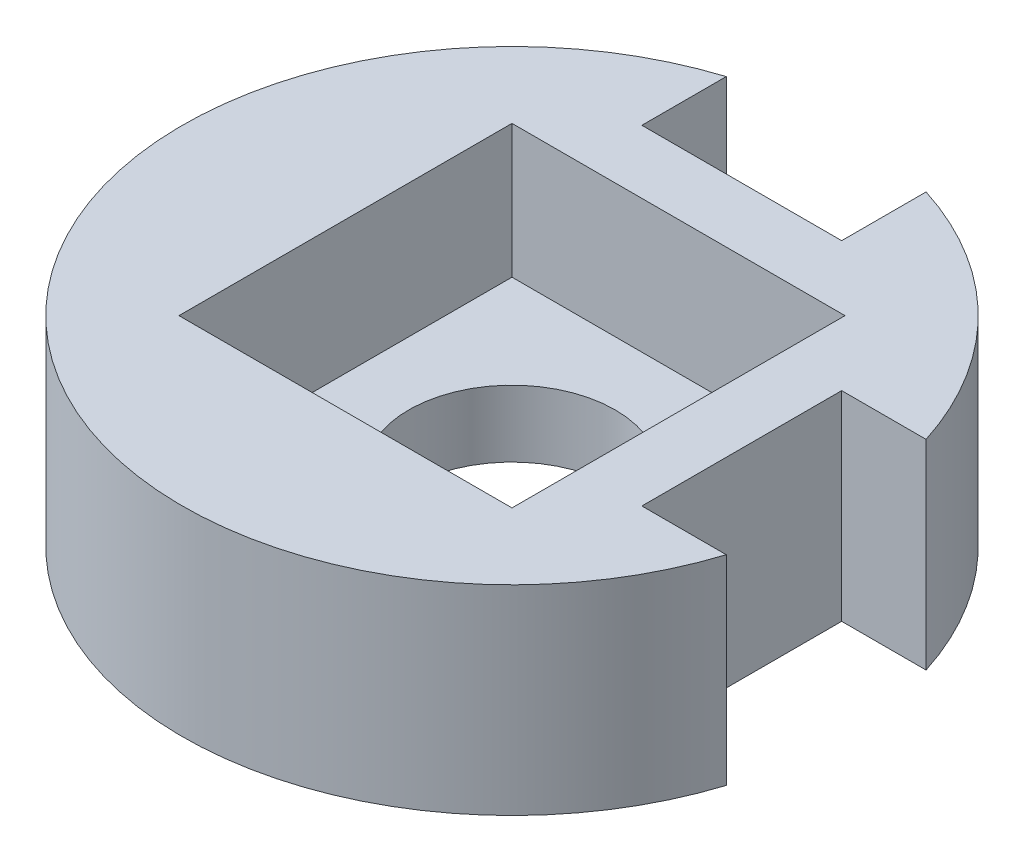
SolidWorks part; units mm, degrees
ref_plane "Front Plane" through (0, 0, 0) normal (0, 0, 1) x (1, 0, 0)
ref_plane "Top Plane" through (0, 0, 0) normal (0, 1, 0) x (1, 0, 0)
ref_plane "Right Plane" through (0, 0, 0) normal (1, 0, 0) x (0, 0, -1)
sketch "Sketch1" plane through (0, 0, 0) normal (0, 1, 0) x (1, 0, 0)
  line L3 (6.9, 3) -> (12.9, 3)
  line L4 (6.9, 3) -> (6.9, -3)
  line L5 (6.9, -3) -> (12.9, -3)
  line L6 (12.9, 3) -> (12.9, -3)
  line L7 (6.9, 3) -> (12.9, -3) construction
  line L8 (6.9, -3) -> (12.9, 3) construction
  line L9 (-3, 12.9) -> (3, 12.9)
  line L10 (-3, 12.9) -> (-3, 6.9)
  line L11 (-3, 6.9) -> (3, 6.9)
  line L12 (3, 12.9) -> (3, 6.9)
  line L13 (-3, 12.9) -> (3, 6.9) construction
  line L14 (-3, 6.9) -> (3, 12.9) construction
  line L15 (-5, 5) -> (5, 5)
  line L16 (-5, 5) -> (-5, -5)
  line L17 (-5, -5) -> (5, -5)
  line L18 (5, 5) -> (5, -5)
  line L19 (-5, 5) -> (5, -5) construction
  line L20 (-5, -5) -> (5, 5) construction
  circle A0 centre (0, 0) radius 9.9
  point P3 (9.9, 0)
  point P12 (0, 9.9)
  dimension "D1" = 19.8
  dimension "D2" = 10
  dimension "D3" = 10
  dimension "D5" = 6
  dimension "D6" = 3
  dimension "D7" = 6
  dimension "D8" = 6
extrude "Boss-Extrude1" add sketch "Sketch1" along normal blind 6
sketch "Sketch3" plane through (0, 0, 0) normal (0, -1, 0) x (1, 0, 0)
  line L1 (-5, 5) -> (5, 5)
  line L2 (-5, 5) -> (-5, -5)
  line L3 (-5, -5) -> (5, -5)
  line L4 (5, 5) -> (5, -5)
  circle A0 centre (0, 0) radius 3.1
  dimension "D1" = 6.2
extrude "Boss-Extrude2" add sketch "Sketch3" against normal blind 2
